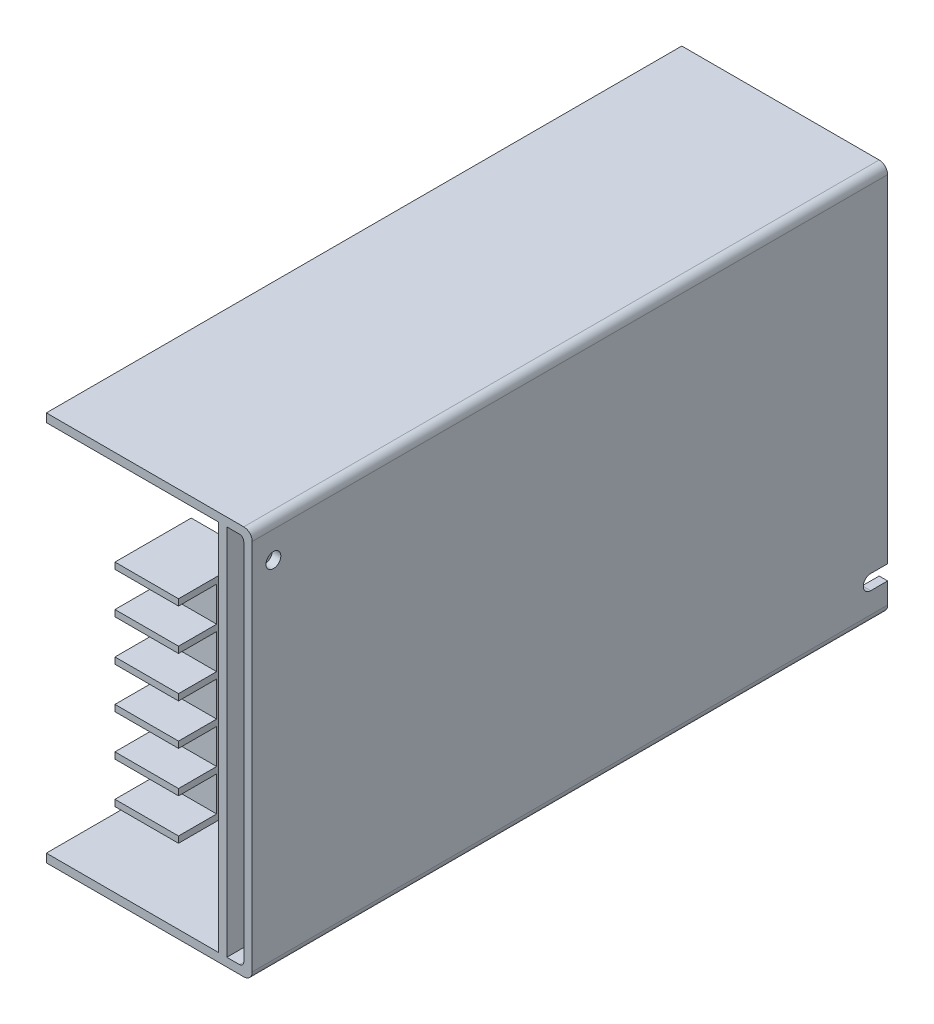
SolidWorks part; units mm, degrees
ref_plane "前视基准面" through (0, 0, 0) normal (0, 0, 1) x (1, 0, 0)
ref_plane "上视基准面" through (0, 0, 0) normal (0, 1, 0) x (1, 0, 0)
ref_plane "右视基准面" through (0, 0, 0) normal (1, 0, 0) x (0, 0, -1)
sketch "草图1" plane through (0, 0, 0) normal (0, 0, 1) x (1, 0, 0)
  line L0 (-24.3, 44) -> (21.3, 44)
  line L1 (22.3, -46) -> (-24.3, -46)
  line L2 (24.3, -44) -> (24.3, 44)
  line L3 (22.3, 46) -> (-24.3, 46)
  line L4 (-24.3, -46) -> (-24.3, -44)
  line L5 (24.3, -46) -> (-24.3, 46) construction
  line L6 (24.3, 46) -> (-24.3, -46) construction
  line L7 (22.3, 43) -> (22.3, -43)
  line L8 (21.3, -44) -> (-24.3, -44)
  line L9 (-24.3, 44) -> (-24.3, 46)
  arc A0 (22.3, -46) -> (24.3, -44) centre (22.3, -44) ccw
  arc A1 (24.3, 44) -> (22.3, 46) centre (22.3, 44) ccw
  arc A2 (22.3, -43) -> (21.3, -44) centre (21.3, -43) cw
  arc A3 (21.3, 44) -> (22.3, 43) centre (21.3, 43) cw
  point P0 (0, 0)
  dimension "D5" = 2
  dimension "D6" = 1
  dimension "D1" = 48.6
  dimension "D2" = 92
  dimension "D3" = 2
  dimension "D4" = 2
extrude "凸台-拉伸1" add sketch "草图1" along normal blind 150
sketch "草图2" plane through (0, 0, 0) normal (0, 0, -1) x (-1, 0, 0)
  line L0 (24.3, 44) -> (-21.3, 44) construction
  line L1 (-16.3, 44) -> (-18.3, 44)
  line L2 (-16.3, 44) -> (-16.3, -44)
  line L3 (-16.3, -44) -> (-18.3, -44)
  line L4 (-18.3, 44) -> (-18.3, -44)
  line L5 (-21.3, -44) -> (24.3, -44) construction
  line L6 (-22.3, 43) -> (-22.3, -43) construction
  dimension "D1" = 4
  dimension "D2" = 2
extrude "凸台-拉伸2" add sketch "草图2" against normal up to surface (150 mm away) up to face at (7.0369, 0, 150)
sketch "草图3" plane through (16.3, 0, 0) normal (-1, 0, 0) x (0, 0, 1)
  line L0 (150, -44) -> (150, 44) construction
  line L1 (66, -5) -> (96, -5)
  line L2 (66, -5) -> (66, -40)
  line L3 (66, -40) -> (96, -40)
  line L4 (96, -5) -> (96, -40)
  line L5 (150, -44) -> (0, -44) construction
  line L8 (150, 44) -> (0, 44) construction
  line L9 (0, -44) -> (0, 44) construction
  line L10 (52.4971, 30.3675) -> (72.5286, 30.3675)
  line L11 (72.5286, 30.3675) -> (72.5286, 27.5989)
  line L12 (72.5286, 27.5989) -> (65.3987, 27.5989)
  line L13 (65.3987, 27.5989) -> (65.3987, 22.2246)
  line L14 (65.3987, 22.2246) -> (72.5286, 22.2246)
  line L15 (72.5286, 22.2246) -> (72.5286, 19.4561)
  line L16 (72.5286, 19.4561) -> (65.3987, 19.4561)
  line L17 (65.3987, 19.4561) -> (65.3987, 15.5475)
  line L18 (65.3987, 15.5475) -> (72.5286, 15.5475)
  line L19 (72.5286, 15.5475) -> (72.5286, 13.756)
  line L20 (72.5286, 13.756) -> (65.3987, 13.756)
  line L21 (65.3987, 13.756) -> (65.3987, 9.196)
  line L22 (65.3987, 9.196) -> (72.5286, 9.196)
  line L23 (72.5286, 9.196) -> (72.5286, 7.2417)
  line L24 (72.5286, 7.2417) -> (52.4971, 7.2417)
  line L25 (52.4971, 7.2417) -> (52.4971, 9.196)
  line L26 (52.4971, 9.196) -> (62.5129, 9.196)
  line L27 (62.5129, 9.196) -> (62.5129, 27.5989)
  line L28 (62.5129, 27.5989) -> (52.4971, 27.5989)
  line L29 (52.4971, 27.5989) -> (52.4971, 30.3675)
  circle A0 centre (27.5, 20.5) radius 15
  circle A1 centre (27.5, -13.5) radius 15
  circle A2 centre (108.1602, -12.5) radius 6.5
  circle A3 centre (121.5, -15.5) radius 6.5
  dimension "D1" = 30
  dimension "D6" = 4
  dimension "D7" = 8.5
  dimension "D9" = 13
  dimension "D10" = 25
  dimension "D11" = 22
  dimension "D12" = 22
  dimension "D13" = 0.6729
  dimension "D2" = 30
  dimension "D3" = 35
  dimension "D4" = 54
  dimension "D5" = 4
  dimension "D8" = 12.5
extrude "凸台-拉伸3" add sketch "草图3" along normal blind 38
sketch "草图4" plane through (16.3, 0, 0) normal (-1, 0, 0) x (0, 0, 1)
  line L0 (159.4, 33) -> (141.4, 33)
  line L1 (141.4, 33) -> (141.4, -17)
  line L2 (141.4, -17) -> (159.4, -17)
  line L3 (159.4, -17) -> (159.4, -15.5)
  line L4 (159.4, -15.5) -> (150.4, -15.5)
  line L5 (150.4, -15.5) -> (150.4, -7.3)
  line L6 (150.4, -7.3) -> (159.4, -7.3)
  line L7 (159.4, -7.3) -> (159.4, -5.8)
  line L8 (159.4, -5.8) -> (150.4, -5.8)
  line L9 (150.4, -5.8) -> (150.4, 2.4)
  line L10 (150.4, 2.4) -> (159.4, 2.4)
  line L11 (159.4, 2.4) -> (159.4, 3.9)
  line L12 (159.4, 3.9) -> (150.4, 3.9)
  line L13 (150.4, 3.9) -> (150.4, 12.1)
  line L14 (150.4, 12.1) -> (159.4, 12.1)
  line L15 (159.4, 12.1) -> (159.4, 13.6)
  line L16 (159.4, 13.6) -> (150.4, 13.6)
  line L21 (150.4, 23.3) -> (159.4, 23.3)
  line L22 (159.4, 23.3) -> (159.4, 21.8)
  line L23 (159.4, 21.8) -> (150.4, 21.8)
  line L24 (150.4, 21.8) -> (150.4, 13.6)
  line L25 (159.4, 33) -> (159.4, 31.5)
  line L26 (159.4, 31.5) -> (150.4, 31.5)
  line L27 (150.4, 31.5) -> (150.4, 23.3)
  line L28 (150, 46) -> (0, 46) construction
  line L30 (150, -44) -> (150, 44) construction
  dimension "D1" = 8.2
  dimension "D2" = 50
  dimension "D3" = 9
  dimension "D4" = 9
  dimension "D5" = 13
  dimension "D6" = 9.4
extrude "凸台-拉伸4" add sketch "草图4" along normal blind 15
sketch "草图5" plane through (24.3, 0, 0) normal (1, 0, 0) x (0, 0, -1)
  line L0 (-4, -35.55) -> (0, -35.55)
  line L1 (-145, 37.7) -> (-4, 37.7) construction
  line L2 (-145, 37.7) -> (-145, -37.3) construction
  line L3 (-145, -37.3) -> (-4, -37.3) construction
  line L4 (-4, 37.7) -> (-4, -37.3) construction
  line L5 (0, -44) -> (0, 44) construction
  line L6 (0, -35.55) -> (0, -39.05)
  line L7 (0, -39.05) -> (-4, -39.05)
  line L8 (-150, -46) -> (0, -46) construction
  line L9 (-150, 46) -> (0, 46) construction
  line L10 (-150, -44) -> (-150, 44) construction
  circle A0 centre (-145, 37.7) radius 1.75
  arc A1 (-4, -35.55) -> (-4, -39.05) centre (-4, -37.3) ccw
  dimension "D3" = 3.5
  dimension "D1" = 141
  dimension "D2" = 75
  dimension "D4" = 4
  dimension "D5" = 8.7
  dimension "D6" = 8.3
  dimension "D7" = 5
extrude "切除-拉伸1" cut sketch "草图5" against normal up to next
sketch "草图6" plane through (0, -46, 0) normal (0, -1, 0) x (1, 0, 0)
  line L0 (-24.3, 150) -> (-24.3, 0) construction
  line L1 (-24.3, 150) -> (22.3, 150) construction
  circle A0 centre (-4.3, 118) radius 2.5
  circle A1 centre (-4.3, 59) radius 2.5
  circle A2 centre (-4.3, 24) radius 2.5
  dimension "D1" = 5
  dimension "D2" = 20
  dimension "D3" = 32
  dimension "D4" = 59
  dimension "D5" = 35
extrude "凸台-拉伸5" add sketch "草图6" along normal blind 3
sketch "草图7" plane through (16.3, 0, 0) normal (-1, 0, 0) x (0, 0, 1)
  line L0 (150, -44) -> (0, -44) construction
  line L1 (9, -44) -> (0, -44)
  line L2 (9, -44) -> (9, 44)
  line L3 (9, 44) -> (0, 44)
  line L4 (0, -44) -> (0, 44)
  dimension "D1" = 9
extrude "切除-拉伸2" cut sketch "草图7" against normal up to next
